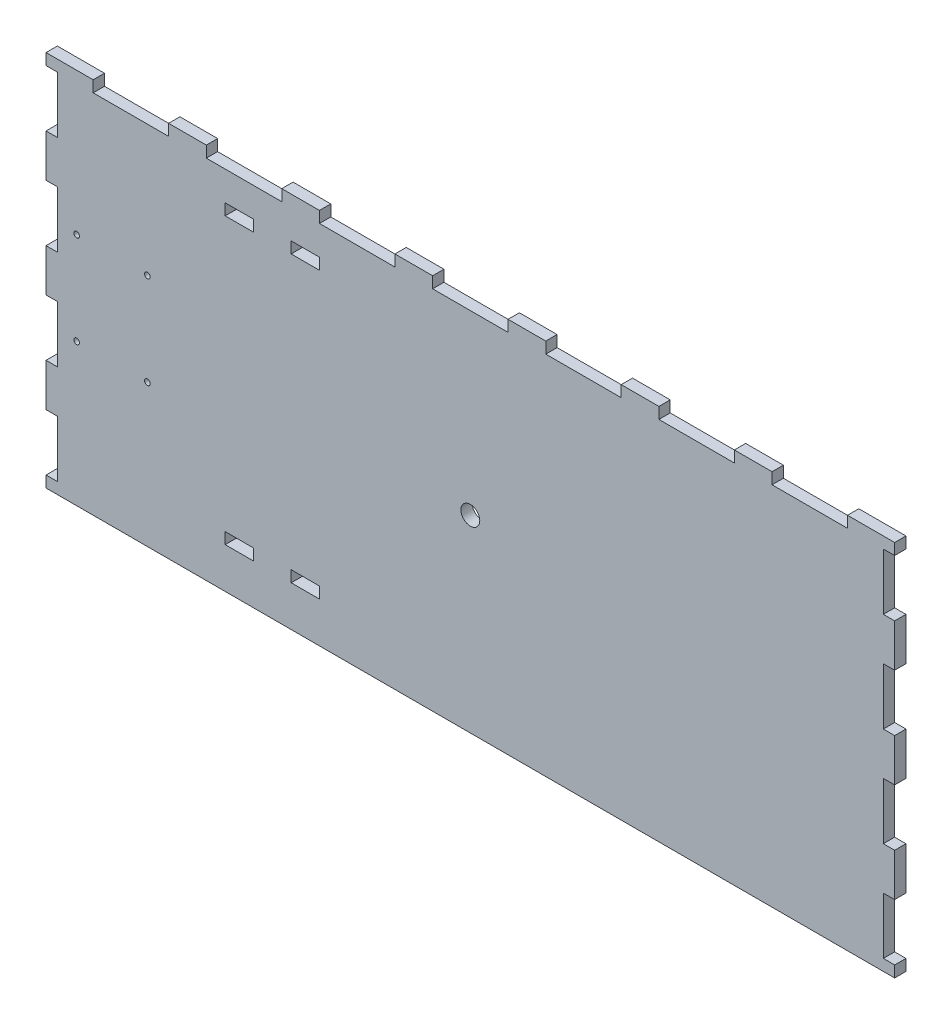
SolidWorks part; units mm, degrees
ref_plane "Plan de face" through (0, 0, 0) normal (0, 0, 1) x (1, 0, 0)
ref_plane "Plan de dessus" through (0, 0, 0) normal (0, 1, 0) x (1, 0, 0)
ref_plane "Plan de droite" through (0, 0, 0) normal (1, 0, 0) x (0, 0, -1)
sketch "Esquisse1" plane through (0, 0, 0) normal (0, 0, 1) x (1, 0, 0)
  line L0 (0, 0) -> (450, 0)
  line L1 (450, 0) -> (450, 6)
  line L7 (0, 200) -> (0, 194)
  line L8 (0, 200) -> (25, 200)
  line L9 (0, 100) -> (450, 100) construction
  line L11 (0, 100) -> (0, 111.3333) construction
  line L34 (95, 172.5) -> (95, 34.7805) construction
  line L35 (145, 27.5) -> (145, 21.5)
  line L36 (95, 172.5) -> (110, 172.5)
  line L37 (95, 172.5) -> (95, 178.5)
  line L38 (95, 178.5) -> (110, 178.5)
  line L39 (110, 172.5) -> (110, 178.5)
  line L40 (130, 172.5) -> (145, 172.5)
  line L41 (130, 172.5) -> (130, 178.5)
  line L42 (130, 178.5) -> (145, 178.5)
  line L43 (145, 172.5) -> (145, 178.5)
  line L44 (130, 21.5) -> (145, 21.5)
  line L45 (130, 27.5) -> (130, 21.5)
  line L46 (130, 27.5) -> (145, 27.5)
  line L47 (110, 27.5) -> (110, 21.5)
  line L48 (95, 21.5) -> (110, 21.5)
  line L49 (95, 27.5) -> (95, 21.5)
  line L50 (95, 27.5) -> (110, 27.5)
  line L53 (25, 200) -> (25, 194)
  line L54 (25, 194) -> (65, 194)
  line L55 (65, 200) -> (65, 194)
  line L56 (85, 200) -> (85, 194)
  line L57 (85, 194) -> (125, 194)
  line L58 (125, 200) -> (125, 194)
  line L60 (145, 200) -> (145, 194)
  line L61 (145, 194) -> (185, 194)
  line L62 (185, 200) -> (185, 194)
  line L64 (205, 200) -> (205, 194)
  line L65 (205, 194) -> (245, 194)
  line L66 (245, 200) -> (245, 194)
  line L68 (265, 200) -> (265, 194)
  line L69 (265, 194) -> (305, 194)
  line L70 (305, 200) -> (305, 194)
  line L72 (325, 200) -> (325, 194)
  line L73 (325, 194) -> (365, 194)
  line L74 (365, 200) -> (365, 194)
  line L76 (385, 200) -> (385, 194)
  line L77 (385, 194) -> (425, 194)
  line L78 (425, 200) -> (425, 194)
  line L79 (65, 200) -> (85, 200)
  line L80 (125, 200) -> (145, 200)
  line L81 (185, 200) -> (205, 200)
  line L82 (245, 200) -> (265, 200)
  line L83 (305, 200) -> (325, 200)
  line L84 (365, 200) -> (385, 200)
  line L85 (425, 200) -> (450, 200)
  line L87 (0, 194) -> (6, 194)
  line L89 (0, 164) -> (6, 164)
  line L90 (6, 194) -> (6, 164)
  line L91 (0, 111.3333) -> (6, 111.3333)
  line L92 (6, 141.3333) -> (6, 111.3333)
  line L94 (0, 58.6667) -> (6, 58.6667)
  line L95 (6, 88.6667) -> (6, 58.6667)
  line L97 (0, 6) -> (6, 6)
  line L98 (6, 36) -> (6, 6)
  line L99 (0, 36) -> (6, 36)
  line L100 (0, 88.6667) -> (6, 88.6667)
  line L101 (0, 141.3333) -> (6, 141.3333)
  line L102 (0, 164) -> (0, 141.3333)
  line L103 (0, 111.3333) -> (0, 88.6667)
  line L104 (450, 141.3333) -> (444, 141.3333)
  line L105 (0, 58.6667) -> (0, 36)
  line L106 (0, 6) -> (0, 0)
  line L107 (225, 0) -> (225, 194) construction
  line L108 (450, 194) -> (444, 194)
  line L110 (450, 164) -> (444, 164)
  line L111 (444, 194) -> (444, 164)
  line L113 (450, 111.3333) -> (444, 111.3333)
  line L114 (444, 141.3333) -> (444, 111.3333)
  line L115 (450, 88.6667) -> (444, 88.6667)
  line L117 (450, 58.6667) -> (444, 58.6667)
  line L118 (444, 88.6667) -> (444, 58.6667)
  line L119 (450, 36) -> (444, 36)
  line L121 (450, 6) -> (444, 6)
  line L122 (444, 36) -> (444, 6)
  line L123 (450, 194) -> (450, 200)
  line L124 (450, 141.3333) -> (450, 164)
  line L125 (450, 88.6667) -> (450, 111.3333)
  line L126 (450, 36) -> (450, 58.6667)
  circle A1 centre (225, 100) radius 5
  circle A2 centre (16.25, 124.5) radius 1.5
  circle A3 centre (53.75, 124.5) radius 1.5
  circle A4 centre (53.75, 75.5) radius 1.5
  circle A5 centre (16.25, 75.5) radius 1.5
  point P26 (102.5, 27.5)
  dimension "D2" = 10
  dimension "D10" = 16.25
  dimension "D14" = 3
  dimension "D15" = 3
  dimension "D1" = 450
  dimension "D3" = 15
  dimension "D4" = 6
  dimension "D5" = 200
  dimension "D6" = 6
  dimension "D7" = 15
  dimension "D8" = 20
  dimension "D9" = 145
  dimension "D11" = 6
  dimension "D12" = 24.5
  dimension "D13" = 37.5
  dimension "D16" = 6
  dimension "D17" = 40
  dimension "D18" = 25
  dimension "D20" = 30
  dimension "D22" = 6
  dimension "D23" = 6
  dimension "D24" = 6
  dimension "D25" = 30
  dimension "D27" = 6
  dimension "D19" = 7
  dimension "D21" = 4
  dimension "D26" = 4
extrude "Boss.-Extru.1" add sketch "Esquisse1" along normal blind 6
